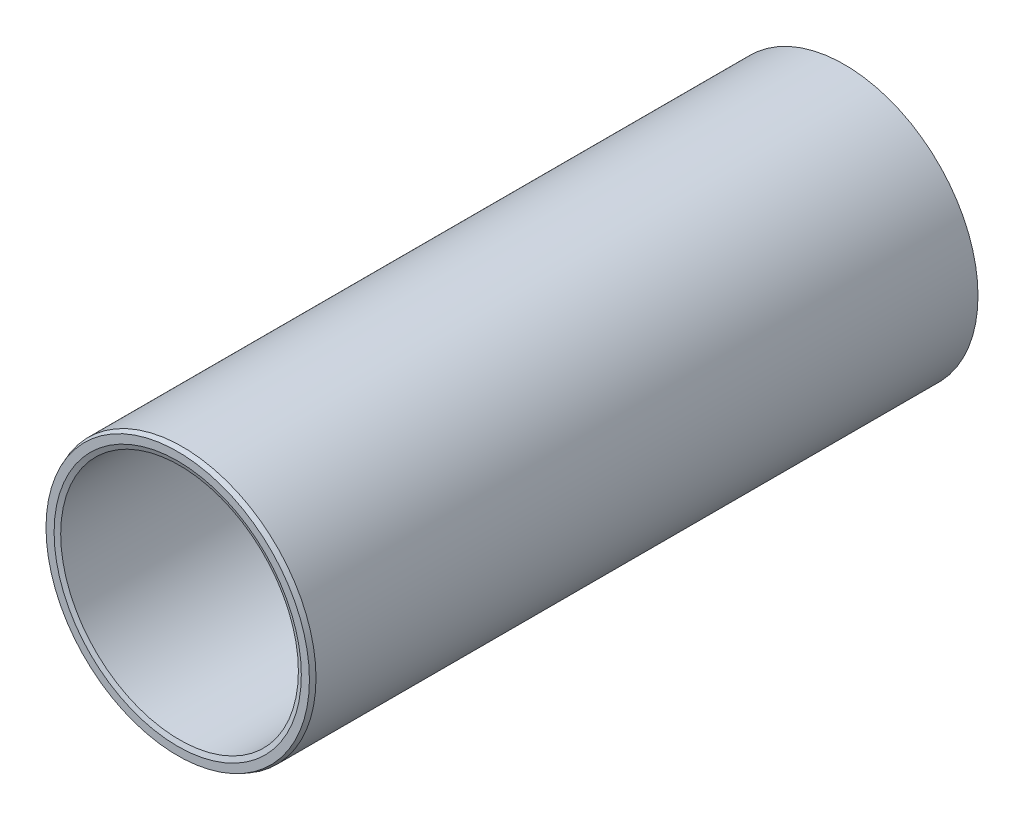
SolidWorks part; units mm, degrees
ref_plane "Alzado" through (0, 0, 0) normal (0, 0, 1) x (1, 0, 0)
ref_plane "Planta" through (0, 0, 0) normal (0, 1, 0) x (1, 0, 0)
ref_plane "Vista lateral" through (0, 0, 0) normal (1, 0, 0) x (0, 0, -1)
sketch "Croquis1" plane through (0, 0, 0) normal (0, 0, 1) x (1, 0, 0)
  circle A0 centre (0, 0) radius 1.1235
  circle A1 centre (0, 0) radius 1
  dimension "D1" = 2.247
  dimension "D2" = 2
extrude "Saliente-Extruir1" add sketch "Croquis1" along normal blind 5.625
chamfer "Chaflán1" distance 0.04 angle 21 4 edges at (1.1235, 0, 0) (1, 0, 0) (1.1235, 0, 5.625) (1, 0, 5.625)
